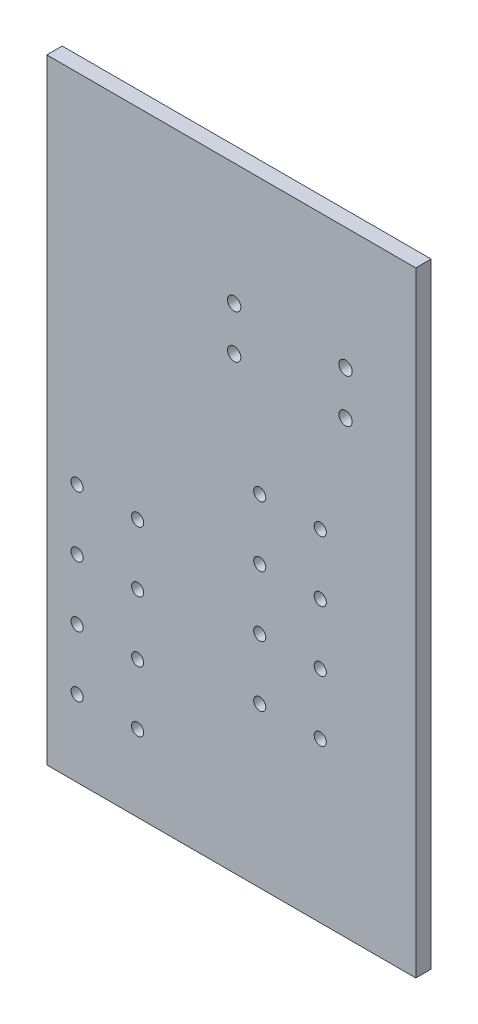
SolidWorks part; units mm, degrees
material "6061 Alloy"
ref_plane "Front Plane" through (0, 0, 0) normal (0, 0, 1) x (1, 0, 0)
ref_plane "Top Plane" through (0, 0, 0) normal (0, 1, 0) x (1, 0, 0)
ref_plane "Right Plane" through (0, 0, 0) normal (1, 0, 0) x (0, 0, -1)
sketch "Sketch1" plane through (0, 0, 0) normal (0, 0, 1) x (1, 0, 0)
  line L1 (-76.2, 127) -> (76.2, 127)
  line L2 (-76.2, 127) -> (-76.2, -127)
  line L3 (-76.2, -127) -> (76.2, -127)
  line L4 (76.2, 127) -> (76.2, -127)
  line L5 (-76.2, 127) -> (76.2, -127) construction
  line L6 (-76.2, -127) -> (76.2, 127) construction
  point P0 (0, 0)
  dimension "D1" = 254
  dimension "D2" = 152.4
extrude "Boss-Extrude1" add sketch "Sketch1" along normal blind 6.35
sketch "Sketch3" plane through (0, 0, 0) normal (0, 0, -1) x (-1, 0, 0)
  circle A0 centre (63.7, -20.45) radius 2.5 construction
  circle A1 centre (63.7, -20.45) radius 2.5
  circle A2 centre (38.7, -20.45) radius 2.5 construction
  circle A3 centre (38.7, -45.45) radius 2.5 construction
  circle A4 centre (63.7, -45.45) radius 2.5 construction
  circle A5 centre (63.7, -70.45) radius 2.5 construction
  circle A6 centre (38.7, -70.45) radius 2.5 construction
  circle A7 centre (38.7, -95.45) radius 2.5 construction
  circle A8 centre (63.7, -95.45) radius 2.5 construction
  circle A9 centre (38.7, -20.45) radius 2.5
  circle A10 centre (38.7, -45.45) radius 2.5
  circle A11 centre (63.7, -45.45) radius 2.5
  circle A12 centre (63.7, -70.45) radius 2.5
  circle A13 centre (38.7, -70.45) radius 2.5
  circle A14 centre (38.7, -95.45) radius 2.5
  circle A15 centre (63.7, -95.45) radius 2.5
  circle A16 centre (-11.738, -61.16) radius 2.5 construction
  circle A17 centre (-11.738, -36.16) radius 2.5 construction
  circle A18 centre (-36.738, -61.16) radius 2.5 construction
  circle A19 centre (-36.738, -36.16) radius 2.5 construction
  circle A20 centre (-11.738, -11.16) radius 2.5 construction
  circle A21 centre (-36.738, -11.16) radius 2.5 construction
  circle A22 centre (-36.738, 13.84) radius 2.5 construction
  circle A23 centre (-11.738, 13.84) radius 2.5 construction
  circle A24 centre (-11.738, -61.16) radius 2.5
  circle A25 centre (-11.738, -36.16) radius 2.5
  circle A26 centre (-36.738, -61.16) radius 2.5
  circle A27 centre (-36.738, -36.16) radius 2.5
  circle A28 centre (-11.738, -11.16) radius 2.5
  circle A29 centre (-36.738, -11.16) radius 2.5
  circle A30 centre (-36.738, 13.84) radius 2.5
  circle A31 centre (-11.738, 13.84) radius 2.5
extrude "Cut-Extrude2" cut sketch "Sketch3" against normal up to next
sketch "Sketch4" plane through (0, 0, 0) normal (0, 0, -1) x (-1, 0, 0)
  circle A0 centre (-47.1805, 58.7624) radius 2.75 construction
  circle A1 centre (-47.1805, 58.7624) radius 2.75
  circle A2 centre (-1.1805, 58.7624) radius 2.75 construction
  circle A3 centre (-1.1805, 58.7624) radius 2.75
  circle A4 centre (-47.1805, 76.7624) radius 2.75 construction
  circle A5 centre (-47.1805, 76.7624) radius 2.75
  circle A6 centre (-1.1805, 76.7624) radius 2.75 construction
  circle A7 centre (-1.1805, 76.7624) radius 2.75
extrude "Cut-Extrude3" cut sketch "Sketch4" against normal up to next
